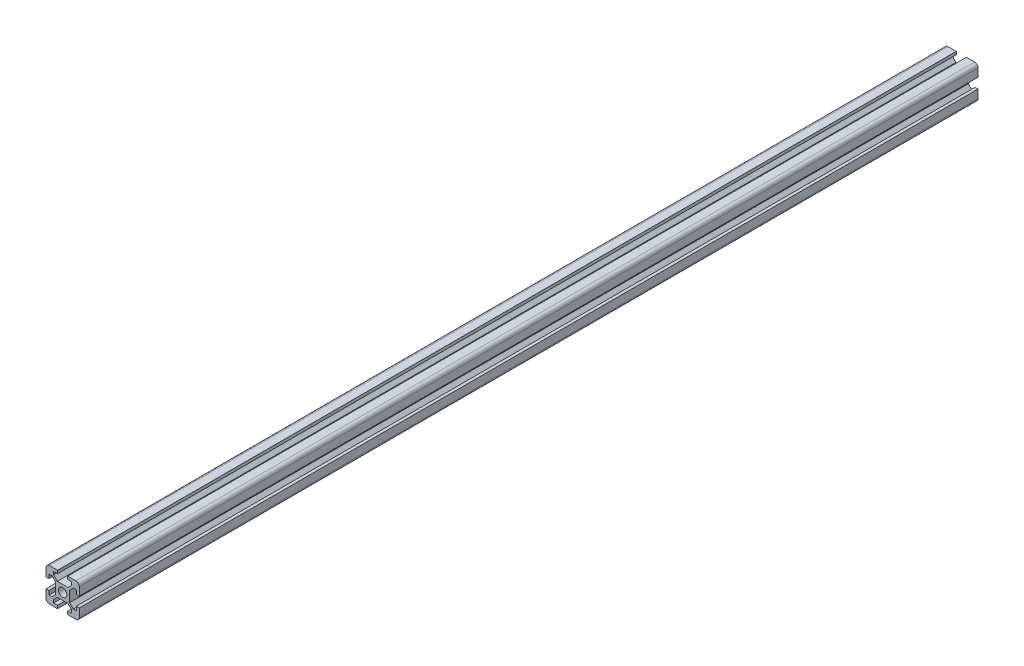
SolidWorks part; units mm, degrees
material "1060 Alloy"
ref_plane "Front Plane" through (0, 0, 0) normal (0, 0, 1) x (1, 0, 0)
ref_plane "Top Plane" through (0, 0, 0) normal (0, 1, 0) x (1, 0, 0)
ref_plane "Right Plane" through (0, 0, 0) normal (1, 0, 0) x (0, 0, -1)
sketch "Sketch1" plane through (0, 0, 0) normal (0, 0, 1) x (1, 0, 0)
  line L0 (-5.46, -6.42) -> (-3.215, -4.175)
  line L1 (-10, -10) -> (-3.06, -10)
  line L2 (-10, -10) -> (-10, -3.06)
  line L3 (-10, 10) -> (-3.06, 10)
  line L4 (10, -10) -> (10, -3.06)
  line L5 (-10, -10) -> (10, 10) construction
  line L6 (-10, 10) -> (10, -10) construction
  line L7 (-3.215, -4.175) -> (3.215, -4.175)
  line L8 (-4.175, -3.215) -> (-4.175, 3.215)
  line L9 (-3.215, 4.175) -> (3.215, 4.175)
  line L10 (4.175, -3.215) -> (4.175, 3.215)
  line L11 (-4.175, -4.175) -> (4.175, 4.175) construction
  line L12 (-4.175, 4.175) -> (4.175, -4.175) construction
  line L13 (-5.46, 6.42) -> (-5.46, 8.22)
  line L14 (-5.46, 8.22) -> (-3.06, 8.22)
  line L15 (-3.06, 8.22) -> (-3.06, 10)
  line L16 (-6.42, -5.46) -> (-4.175, -3.215)
  line L17 (5.46, 6.42) -> (5.46, 8.22)
  line L18 (5.46, 8.22) -> (3.06, 8.22)
  line L19 (3.06, 8.22) -> (3.06, 10)
  line L20 (-5.46, 6.42) -> (-3.215, 4.175)
  line L21 (6.42, 5.46) -> (8.22, 5.46)
  line L22 (8.22, 5.46) -> (8.22, 3.06)
  line L23 (8.22, 3.06) -> (10, 3.06)
  line L24 (8.22, -5.46) -> (6.42, -5.46)
  line L25 (-6.42, 5.46) -> (-4.175, 3.215)
  line L26 (8.22, -5.46) -> (8.22, -3.06)
  line L27 (8.22, -3.06) -> (10, -3.06)
  line L28 (5.46, 6.42) -> (3.215, 4.175)
  line L29 (5.46, -6.42) -> (5.46, -8.22)
  line L30 (5.46, -8.22) -> (3.06, -8.22)
  line L31 (3.06, -8.22) -> (3.06, -10)
  line L32 (6.42, 5.46) -> (4.175, 3.215)
  line L33 (-6.42, 5.46) -> (-8.22, 5.46)
  line L34 (-8.22, 5.46) -> (-8.22, 3.06)
  line L35 (-8.22, 3.06) -> (-10, 3.06)
  line L36 (6.42, -5.46) -> (4.175, -3.215)
  line L37 (-6.42, -5.46) -> (-8.22, -5.46)
  line L38 (-8.22, -5.46) -> (-8.22, -3.06)
  line L39 (-8.22, -3.06) -> (-10, -3.06)
  line L40 (5.46, -6.42) -> (3.215, -4.175)
  line L41 (-5.46, -6.42) -> (-5.46, -8.22)
  line L42 (-5.46, -8.22) -> (-3.06, -8.22)
  line L43 (-3.06, -8.22) -> (-3.06, -10)
  line L44 (-10, 3.06) -> (-10, 10)
  line L45 (3.06, 10) -> (10, 10)
  line L46 (10, 3.06) -> (10, 10)
  line L47 (3.06, -10) -> (10, -10)
  circle A0 centre (0, 0) radius 2.5
  point P0 (0, 0)
  dimension "D3" = 5
  dimension "D1" = 20
  dimension "D2" = 20
  dimension "D4" = 8.35
  dimension "D5" = 8.35
  dimension "D6" = 6.94
  dimension "D7" = 1.78
  dimension "D8" = 2.4
  dimension "D9" = 1.8
extrude "Boss-Extrude1" add sketch "Sketch1" along normal blind 540
fillet "Fillet1" radius 2 4 edges at (-10, -10, 270) (10, -10, 270) (-10, 10, 270) (10, 10, 270)
ref_plane "Plane1" through (0, 0, 270) normal (0, 0, 1) x (1, 0, 0)
